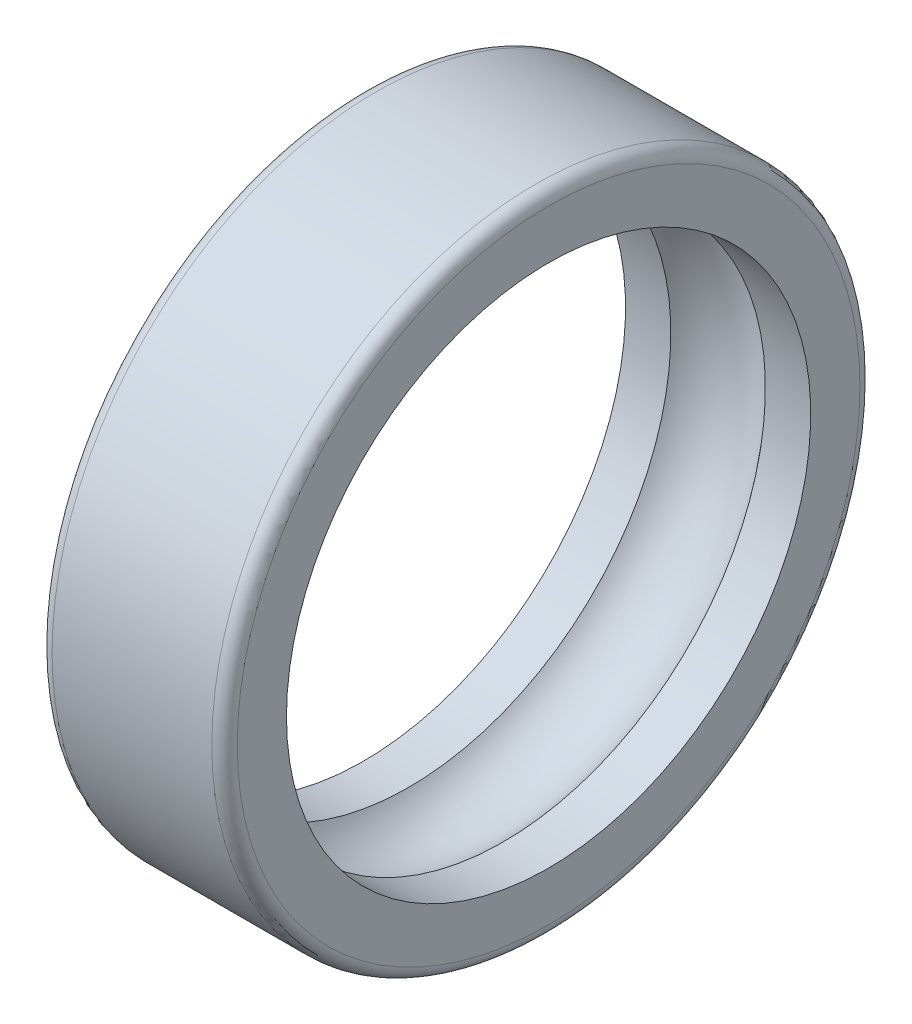
SolidWorks part; units mm, degrees
ref_plane "Front Plane" through (0, 0, 0) normal (0, 0, 1) x (1, 0, 0)
ref_plane "Top Plane" through (0, 0, 0) normal (0, 1, 0) x (1, 0, 0)
ref_plane "Right Plane" through (0, 0, 0) normal (1, 0, 0) x (0, 0, -1)
ref_plane "Plane1"
sketch "Sketch1" plane through (0, 0, 0) normal (0, 0, 1) x (1, 0, 0)
  line L0 (0, 26.9) -> (0, 22.65)
  line L1 (0, 22.65) -> (3.9137, 22.65)
  line L2 (12.0863, 22.65) -> (16, 22.65)
  line L3 (16, 22.65) -> (16, 26.9)
  line L4 (14.9, 28) -> (1.1, 28)
  line L5 (200, 0) -> (-200, 0) construction
  arc A0 (12.0863, 22.65) -> (3.9137, 22.65) centre (8, 19.5) ccw
  arc A1 (16, 26.9) -> (14.9, 28) centre (14.9, 26.9) ccw
  arc A2 (1.1, 28) -> (0, 26.9) centre (1.1, 26.9) ccw
revolve "Revolução1" add sketch "Sketch1" angle 360 about L5
